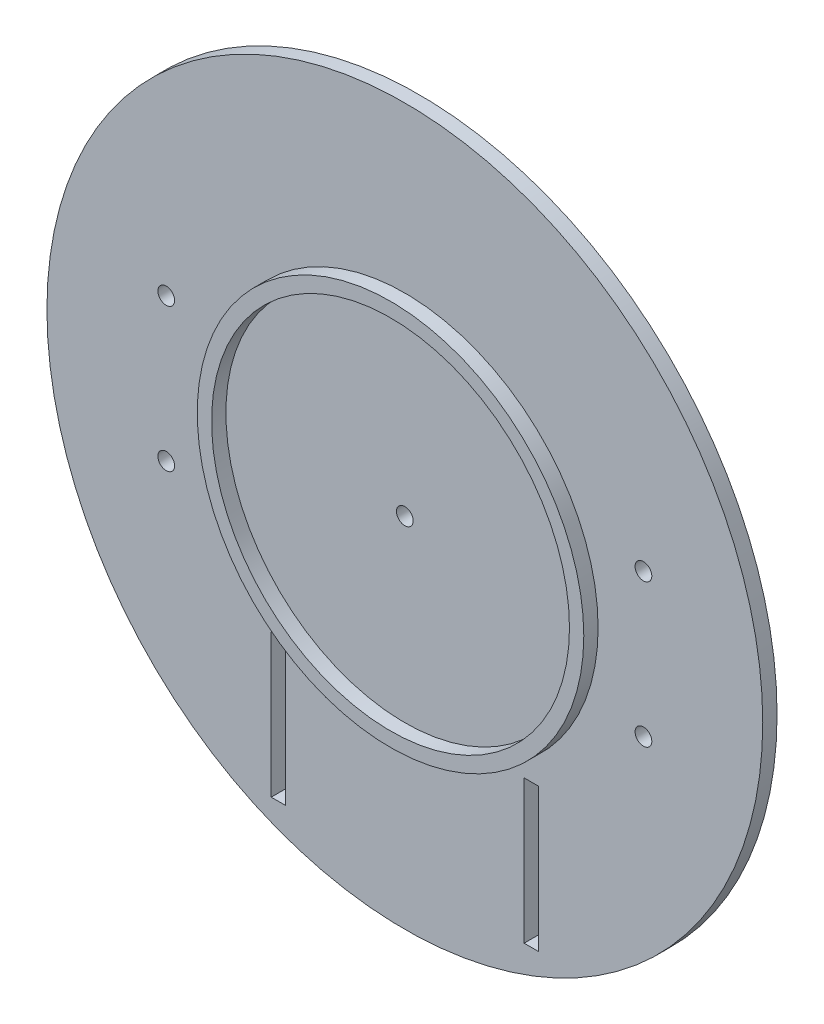
SolidWorks part; units mm, degrees
ref_plane "Front Plane" through (0, 0, 0) normal (0, 0, 1) x (1, 0, 0)
ref_plane "Top Plane" through (0, 0, 0) normal (0, 1, 0) x (1, 0, 0)
ref_plane "Right Plane" through (0, 0, 0) normal (1, 0, 0) x (0, 0, -1)
sketch "Sketch1" plane through (0, 0, 0) normal (0, 0, 1) x (1, 0, 0)
  circle A0 centre (0, 0) radius 75
  dimension "D1" = 150
extrude "Boss-Extrude1" add sketch "Sketch1" along normal blind 3
sketch "Sketch2" plane through (0, 0, 3) normal (0, 0, 1) x (1, 0, 0)
  line L1 (-50, 15) -> (50, 15) construction
  line L2 (-50, 15) -> (-50, -15) construction
  line L3 (-50, -15) -> (50, -15) construction
  line L4 (50, 15) -> (50, -15) construction
  line L5 (-50, 15) -> (50, -15) construction
  line L6 (-50, -15) -> (50, 15) construction
  circle A0 centre (-50, 15) radius 1.75
  circle A1 centre (-50, -15) radius 1.75
  circle A2 centre (50, -15) radius 1.75
  circle A3 centre (50, 15) radius 1.75
  circle A4 centre (0, 0) radius 1.75
  point P0 (0, 0)
  dimension "D3" = 3.5
  dimension "D1" = 100
  dimension "D2" = 30
extrude "Cut-Extrude1" cut sketch "Sketch2" against normal through all
sketch "Sketch3" plane through (0, 0, 3) normal (0, 0, 1) x (1, 0, 0)
  circle A0 centre (0, 0) radius 37.5
  circle A1 centre (0, 0) radius 40.5
  dimension "D1" = 75
  dimension "D2" = 3
extrude "Boss-Extrude2" add sketch "Sketch3" along normal blind 3
sketch "Sketch4" plane through (0, 0, 0) normal (0, 0, -1) x (-1, 0, 0)
  line L0 (0, -50) -> (0, 0) construction
  line L1 (-25, -35) -> (25, -35) construction
  line L2 (-25, -35) -> (-25, -65)
  line L3 (-25, -65) -> (25, -65) construction
  line L4 (25, -35) -> (25, -65)
  line L5 (-25, -35) -> (25, -65) construction
  line L6 (-25, -65) -> (25, -35) construction
  line L8 (25, -35) -> (28, -35)
  line L9 (25, -35) -> (25, -65)
  line L10 (25, -65) -> (28, -65)
  line L11 (28, -35) -> (28, -65)
  line L12 (-25, -35) -> (-28, -35)
  line L13 (-25, -35) -> (-25, -65)
  line L14 (-25, -65) -> (-28, -65)
  line L15 (-28, -35) -> (-28, -65)
  point P0 (0, -50)
  dimension "D1" = 3
  dimension "D2" = 50
  dimension "D3" = 30
  dimension "D4" = 35
extrude "Cut-Extrude2" cut sketch "Sketch4" against normal through all contours L12 L15 L14 L2 | L11 L8 L4 L10
